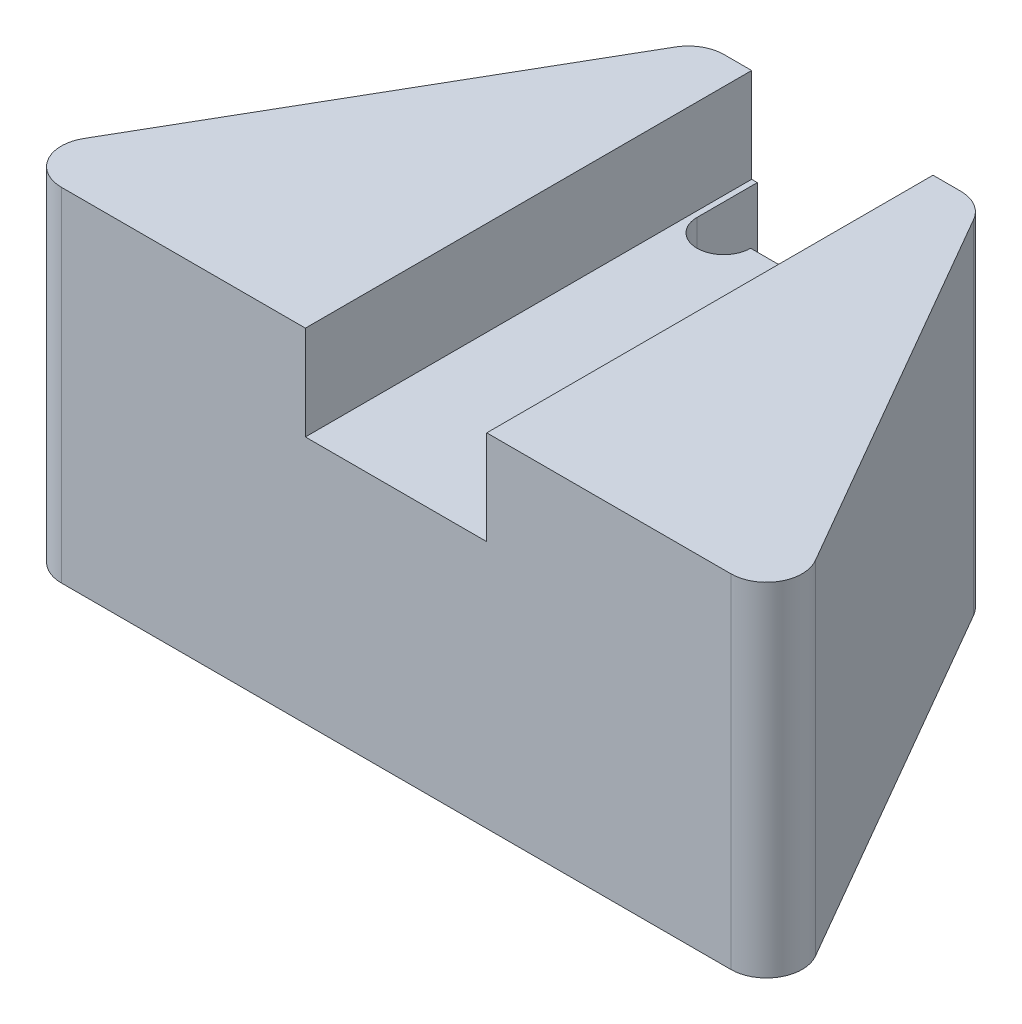
SolidWorks part; units mm, degrees
material "Macor"
ref_plane "Front Plane" through (0, 0, 0) normal (0, 0, 1) x (1, 0, 0)
ref_plane "Top Plane" through (0, 0, 0) normal (0, 1, 0) x (1, 0, 0)
ref_plane "Right Plane" through (0, 0, 0) normal (1, 0, 0) x (0, 0, -1)
sketch "Sketch1" plane through (0, 0, 0) normal (0, 1, 0) x (1, 0, 0)
  line L1 (-14.2978, -12.5) -> (14.2978, -12.5)
  line L2 (-14.2978, -12.5) -> (-14.2978, 12.5) construction
  line L3 (-14.2978, 12.5) -> (14.2978, 12.5) construction
  line L4 (14.2978, -12.5) -> (14.2978, 12.5) construction
  line L5 (-14.2978, -12.5) -> (14.2978, 12.5) construction
  line L6 (-14.2978, 12.5) -> (14.2978, -12.5) construction
  line L8 (-7.7831, 12.5) -> (7.7831, 12.5)
  line L11 (0, 11.2271) -> (0, -49988.7729) construction
  line L14 (-7.7831, 12.5) -> (-22.2169, -12.5)
  line L15 (-22.2169, -12.5) -> (-14.2978, -12.5)
  line L16 (7.7831, 12.5) -> (22.2169, -12.5)
  line L17 (22.2169, -12.5) -> (14.2978, -12.5)
  line L24 (15, 0) -> (-15, 0) construction
  point P0 (0, 0)
  point P14 (0, 12.5)
  dimension "D1" = 25
  dimension "D2" = 30
  dimension "D4" = 60
extrude "Boss-Extrude1" add sketch "Sketch1" along normal mid plane 19.2
ref_plane "Plane1" [suppressed] through (12.8676, 0, -7.7206) normal (0.8575, 0, -0.5145) x (-0.5145, 0, -0.8575)
sketch "Sketch8" [suppressed] plane through (12.8676, 0, -7.7206) normal (0.8575, 0, -0.5145) x (-0.5145, 0, -0.8575)
  line L0 (5.5737, -10.325) -> (15.8636, -10.325) construction
  line L1 (-23.5811, 10.325) -> (5.5737, 10.325)
  line L2 (-23.5811, 10.325) -> (-23.5811, -10.325)
  line L3 (-23.5811, -10.325) -> (5.5737, -10.325)
  line L4 (5.5737, 10.325) -> (5.5737, -10.325)
sketch "Sketch5" [suppressed] plane through (0, 10.325, 0) normal (0, 1, 0) x (1, 0, 0)
  line L0 (-13.9562, 2.5) -> (-14.6634, 3.2071) construction
  line L1 (-13.9562, 2.5) -> (-13.9562, 5.5) construction
  line L2 (-13.9562, 2.5) -> (-15, 2.5) construction
  line L3 (0, 0) -> (0, 50000) construction
  circle A0 centre (-14.6634, 3.2071) radius 1
  circle A1 centre (14.6634, 3.2071) radius 1
  point P2 (-13.9562, 3.9142)
  point P3 (-15.3705, 2.5)
  point P4 (-13.9562, 2.5)
  dimension "D1" = 2
  dimension "D2" = 45
extrude "Cut-Extrude5" [suppressed] cut sketch "Sketch5" against normal through all both and the other way through all
fillet "Fillet5" radius 2 4 edges at (22.2169, 0, 12.5) (-22.2169, 0, 12.5) (-7.7831, 0, -12.5) (7.7831, 0, -12.5)
sketch "Sketch6" [suppressed] plane through (0, 10.325, 0) normal (0, 1, 0) x (1, 0, 0)
  line L1 (-14.054, 4) -> (-7.5, 4)
  line L2 (-7.5, 4) -> (-7.5, 1)
  line L3 (-7.5, 1) -> (-16, 1)
  line L5 (-15.1213, 2.3181) -> (-16, 1)
  line L6 (-15.1213, 2.3181) -> (-22.9271, -9.3906) construction
  line L8 (22.9271, -9.3906) -> (15.1213, 2.3181) construction
  line L9 (16, 1) -> (15.1213, 2.3181)
  line L10 (14.054, 4) -> (7.5, 4)
  line L11 (7.5, 4) -> (7.5, 1)
  line L12 (7.5, 1) -> (16, 1)
  line L13 (9.2062, 12.5) -> (-9.2062, 12.5) construction
  arc A0 (-15.1213, 2.3181) -> (-13.9562, 3.9142) centre (-14.6634, 3.2071) ccw construction
  arc A1 (13.9562, 3.9142) -> (15.1213, 2.3181) centre (14.6634, 3.2071) ccw construction
  arc A2 (-14.054, 4) -> (-15.1213, 2.3181) centre (-14.6634, 3.2071) cw
  arc A3 (14.054, 4) -> (15.1213, 2.3181) centre (14.6634, 3.2071) ccw
  dimension "D1" = 8.5
  dimension "D2" = 15
  dimension "D3" = 3
extrude "Boss-Extrude2" [suppressed] add sketch "Sketch6" along normal blind 2
sketch "Sketch7" plane through (0, 0, 12.5) normal (0, 0, 1) x (1, 0, 0)
  line L0 (-18.7528, 9.6) -> (18.7528, 9.6) construction
  line L1 (-5.08, 9.6) -> (5.08, 9.6)
  line L2 (-5.08, 9.6) -> (-5.08, 4.32)
  line L3 (-5.08, 4.32) -> (5.08, 4.32)
  line L4 (5.08, 9.6) -> (5.08, 4.32)
  point P6 (0, 9.6)
  point P7 (0, 9.6)
  dimension "D1" = 10.16
  dimension "D2" = 5.28
extrude "Cut-Extrude6" cut sketch "Sketch7" against normal through all
sketch "Sketch9" plane through (0, 0, -12.5) normal (0, 0, -1) x (-1, 0, 0)
  line L1 (-3.175, 4.32) -> (3.175, 4.32)
  line L2 (-3.175, 4.32) -> (-3.175, -2.03)
  line L3 (-3.175, -2.03) -> (3.175, -2.03)
  line L4 (3.175, 4.32) -> (3.175, -2.03)
  line L6 (5.08, 4.32) -> (-5.08, 4.32) construction
  point P14 (0, 4.32)
  dimension "D1" = 6.35
extrude "Cut-Extrude7" [suppressed] cut sketch "Sketch9" against normal blind 2.5876
sketch "Sketch10" [suppressed] plane through (0, 0, -12.5) normal (0, 0, -1) x (-1, 0, 0)
  line L1 (-3.9751, 7.55) -> (3.9751, 7.55)
  line L2 (-3.9751, 7.55) -> (-3.9751, 1.2)
  line L3 (-3.9751, 1.2) -> (3.9751, 1.2)
  line L4 (3.9751, 7.55) -> (3.9751, 1.2)
  line L7 (3.175, 7.55) -> (-3.175, 7.55) construction
  line L9 (-3.175, 1.2) -> (3.175, 1.2) construction
  point P9 (0, 1.2)
  dimension "D1" = 7.9502
extrude "Cut-Extrude8" [suppressed] cut sketch "Sketch10" against normal blind 1.0001
sketch "Sketch11" plane through (0, 0, -12.5) normal (0, 0, -1) x (-1, 0, 0)
  line L0 (5.08, 4.32) -> (-5.08, 4.32) construction
  line L1 (-4.7625, 4.32) -> (4.7625, 4.32)
  line L2 (-4.7625, 4.32) -> (-4.7625, -5.205)
  line L3 (-4.7625, -5.205) -> (4.7625, -5.205)
  line L4 (4.7625, 4.32) -> (4.7625, -5.205)
  point P6 (0, 4.32)
  point P7 (0, 4.32)
  dimension "D1" = 9.525
extrude "Cut-Extrude9" cut sketch "Sketch11" against normal blind 3.375
fillet "Fillet6" [suppressed] radius 1.5
sketch "Sketch12" plane through (0, 4.32, 0) normal (0, 1, 0) x (1, 0, 0)
  line L0 (-4.7625, 9.125) -> (4.7625, 9.125) construction
  circle A0 centre (3.2625, 9.125) radius 1.5
  circle A1 centre (-3.2625, 9.125) radius 1.5
  dimension "D1" = 3
extrude "Cut-Extrude10" cut sketch "Sketch12" against normal up to surface (9.525 mm away) up to face at (0, -5.205, -10.8125)
sketch "Sketch13" plane through (0, -9.6, 0) normal (0, -1, 0) x (1, 0, 0)
  line L0 (-15, 0) -> (15, 0)
  line L1 (-8.3605, -11.5) -> (-20.4848, 9.5) construction
  line L2 (20.4848, 9.5) -> (8.3605, -11.5) construction
  line L3 (6.6284, -12.5) -> (-6.6284, -12.5) construction
  dimension "D1" = 12.5
split line "Split Line1"
equation "\"panel_width\"= 5.5in"
equation "\"finger_joint_width\"= 30mm"
